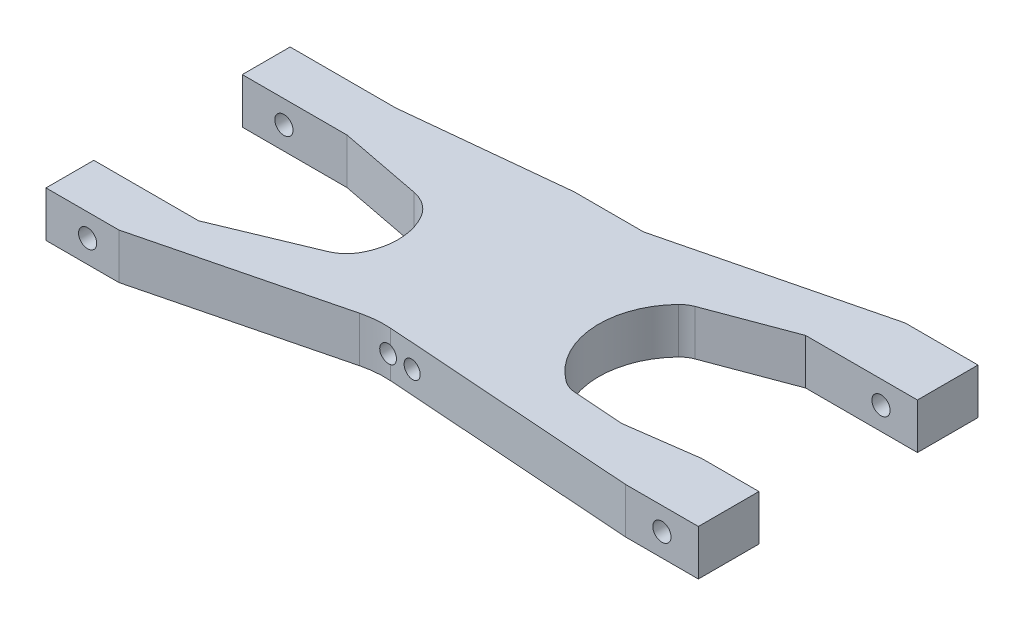
SolidWorks part; units mm, degrees
ref_plane "Front Plane" through (0, 0, 0) normal (0, 0, 1) x (1, 0, 0)
ref_plane "Top Plane" through (0, 0, 0) normal (0, 1, 0) x (1, 0, 0)
ref_plane "Right Plane" through (0, 0, 0) normal (1, 0, 0) x (0, 0, -1)
sketch "Sketch1" plane through (0, 0, 0) normal (0, 1, 0) x (1, 0, 0)
  line L0 (0, 0) -> (0, 38.989)
  line L1 (-86.36, 29.4386) -> (-71.628, 29.4386)
  line L2 (-86.36, 29.4386) -> (-86.36, -4.5974)
  line L3 (0, 0) -> (-10.16, 0)
  line L4 (-71.628, 29.4386) -> (-10.16, 38.989)
  line L5 (0, 38.989) -> (-10.16, 38.989)
  line L6 (-76.2, -4.5974) -> (-10.16, 0)
  line L8 (-86.36, -4.5974) -> (-76.2, -4.5974)
  dimension "D1" = 38.989
  dimension "D2" = 34.036
  dimension "D3" = 86.36
  dimension "D4" = 9.5504
  dimension "D5" = 4.5974
  dimension "D6" = 61.468
  dimension "D7" = 10.16
  dimension "D8" = 10.16
  dimension "D9" = 10.16
extrude "Boss-Extrude1" add sketch "Sketch1" along normal blind 6.35
sketch "Sketch2" plane through (-0.605, 0, 0) normal (0, 0, -1) x (-1, 0, 0)
  line L0 (-0.605, 6.35) -> (-0.605, 0) construction
  line L1 (85.755, 6.35) -> (85.755, 0) construction
  circle A0 centre (4.475, 3.175) radius 1.27
  circle A1 centre (79.9494, 3.175) radius 1.27
  point P9 (0, 0)
  dimension "D1" = 2.54
  dimension "D2" = 2.54
  dimension "D3" = 5.08
  dimension "D4" = 75.4744
  dimension "D5" = 5.8056
extrude "Cut-Extrude2" cut sketch "Sketch2" along normal through all and the other way through all
sketch "Sketch3" plane through (0, 0, 0) normal (0, 1, 0) x (1, 0, 0)
  line L0 (-81.915, 22.7711) -> (-71.755, 22.7711)
  line L1 (0, 30.5435) -> (0, 8.4455)
  line L2 (-10.668, 19.4945) -> (-35.4657, 19.4945) construction
  line L3 (-81.915, 22.7711) -> (-81.915, 2.0701)
  line L4 (-71.755, 2.0701) -> (-81.915, 2.0701)
  line L5 (-71.755, 22.7711) -> (-58.4876, 20.2076)
  line L6 (-71.114, 12.4206) -> (-37.8214, 12.4206) construction
  line L7 (0, 30.5435) -> (-7.9756, 30.5435)
  line L8 (-7.9756, 8.4455) -> (-17.7396, 7.0963)
  line L9 (-7.9756, 8.4455) -> (0, 8.4455)
  line L10 (-71.755, 2.0701) -> (-57.7774, 7.8837)
  line L11 (0, 38.989) -> (-10.16, 38.989) construction
  line L13 (-17.7396, 7.0963) -> (-24.7644, 7.5875)
  line L14 (-15.5852, 30.5435) -> (-26.7956, 26.3446)
  line L15 (-7.9756, 30.5435) -> (-15.5852, 30.5435)
  line L17 (-71.628, 29.4386) -> (-86.36, 29.4386) construction
  arc A0 (-58.4876, 20.2076) -> (-57.7774, 7.8837) centre (-64.2945, 13.6906) cw
  arc A1 (-26.7699, 8.3292) -> (-28.2109, 25.4119) centre (-19.956, 17.5061) cw
  arc A2 (-24.7644, 7.5875) -> (-26.7699, 8.3292) centre (-24.4986, 11.3882) cw
  arc A3 (-26.7956, 26.3446) -> (-28.2109, 25.4119) centre (-25.4593, 22.7767) ccw
  point P18 (-25.7556, 7.6568)
  point P27 (-27.524, 26.0718)
  dimension "D9" = 12.3444
  dimension "D10" = 13.5128
  dimension "D19" = 3.81
  dimension "D20" = 11.43
  dimension "D1" = 20.701
  dimension "D3" = 8.4455
  dimension "D4" = 10.16
  dimension "D5" = 22.098
  dimension "D6" = 6.6675
  dimension "D8" = 7.9756
  dimension "D11" = 18.415
  dimension "D16" = 15.1384
extrude "Cut-Extrude5" cut sketch "Sketch3" along normal through all
sketch "Sketch5" plane through (0, 6.35, 0) normal (0, 1, 0) x (1, 0, 0)
  line L0 (-10.16, 38.989) -> (-53.7874, 28.1798)
  line L1 (-53.7874, 28.1798) -> (-71.628, 29.4386)
  line L2 (-71.628, 29.4386) -> (-10.16, 38.989)
  line L3 (-10.16, 0) -> (-47.3941, 2.6271)
  line L4 (-47.3941, 2.6271) -> (-76.2, -4.5974)
  line L5 (-76.2, -4.5974) -> (-10.16, 0)
extrude "Cut-Extrude7" cut sketch "Sketch5" against normal blind 25.4
ref_plane "Plane1" through (0, 0, -31.75) normal (0, 0, 1) x (1, 0, 0)
sketch "Sketch6" plane through (0, 0, -31.75) normal (0, 0, 1) x (1, 0, 0)
  line L0 (-45.72, 3.1087) -> (-42.164, 3.1087) construction
  line L3 (-38.5716, 6.35) -> (-38.5716, 0)
  line L4 (-10.16, 6.35) -> (-10.16, 0) construction
  line L5 (-53.7874, 6.35) -> (-10.16, 6.35) construction
  line L6 (-53.7874, 0) -> (-10.16, 0) construction
  line L7 (-38.5716, 0) -> (-49.0502, 0)
  line L8 (-49.0502, 0) -> (-49.0502, 6.35)
  line L9 (-49.0502, 6.35) -> (-38.5716, 6.35)
  circle A2 centre (-45.72, 3.1087) radius 1.0795
  circle A3 centre (-42.164, 3.1087) radius 1.0795
  point P2 (-43.942, 3.1087)
  point P11 (-10.16, 3.175)
  dimension "D3" = 2.159
  dimension "D4" = 32.004
extrude "Boss-Extrude2" add sketch "Sketch6" along normal blind 12.7
fillet "Fillet5" radius 12.7 2 edges at (-53.7874, 3.175, -28.1798) (-47.3941, 3.175, -2.6271)
fillet "Fillet6" radius 5.08 2 edges at (-57.7774, 3.175, -7.8837) (-58.4876, 3.175, -20.2076)
sketch "Sketch9" plane through (0, 6.35, 0) normal (0, 1, 0) x (1, 0, 0)
  line L0 (-49.0502, 31.75) -> (-71.628, 29.4386)
  line L1 (-71.628, 29.4386) -> (-71.628, 26.6974)
  line L2 (-71.628, 26.6974) -> (-49.0502, 26.6974)
  line L3 (-49.0502, 26.6974) -> (-49.0502, 31.75)
extrude "Boss-Extrude3" add sketch "Sketch9" against normal up to surface (6.35 mm away) up to face at (-34.6879, 0, -18.1032)
sketch "Sketch10" plane through (0, 0, -31.75) normal (0, 0, -1) x (-1, 0, 0)
  circle A0 centre (42.164, 3.1087) radius 1.2065
  circle A1 centre (45.72, 3.1087) radius 1.2065
extrude "Cut-Extrude9" cut sketch "Sketch10" against normal through all
sketch "Sketch12" plane through (0, 0, 0) normal (0, 1, 0) x (1, 0, 0)
  line L1 (-81.915, 22.7711) -> (-97.6062, 22.7711)
  line L2 (-81.915, 22.7711) -> (-81.915, 2.0701)
  line L3 (-81.915, 2.0701) -> (-97.6062, 2.0701)
  line L4 (-97.6062, 22.7711) -> (-97.6062, 2.0701)
extrude "Cut-Extrude10" cut sketch "Sketch12" along normal through all
